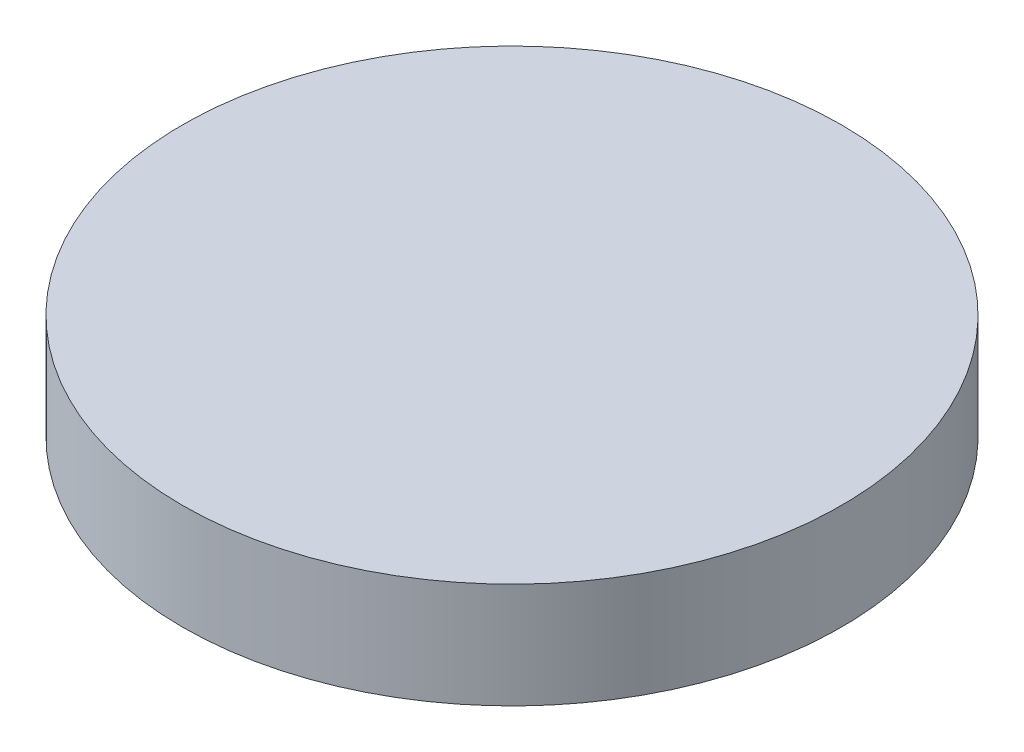
SolidWorks part; units mm, degrees
ref_plane "Front Plane" through (0, 0, 0) normal (0, 0, 1) x (1, 0, 0)
ref_plane "Top Plane" through (0, 0, 0) normal (0, 1, 0) x (1, 0, 0)
ref_plane "Right Plane" through (0, 0, 0) normal (1, 0, 0) x (0, 0, -1)
sketch "Sketch1" plane through (0, 0, 0) normal (0, 1, 0) x (1, 0, 0)
  circle A0 centre (0, 0) radius 12.5
  dimension "D1" = 25
extrude "Boss-Extrude1" add sketch "Sketch1" along normal blind 4
sketch "Sketch3" plane through (0, 4, 0) normal (0, 1, 0) x (1, 0, 0)
  point P0 (0, 0)
